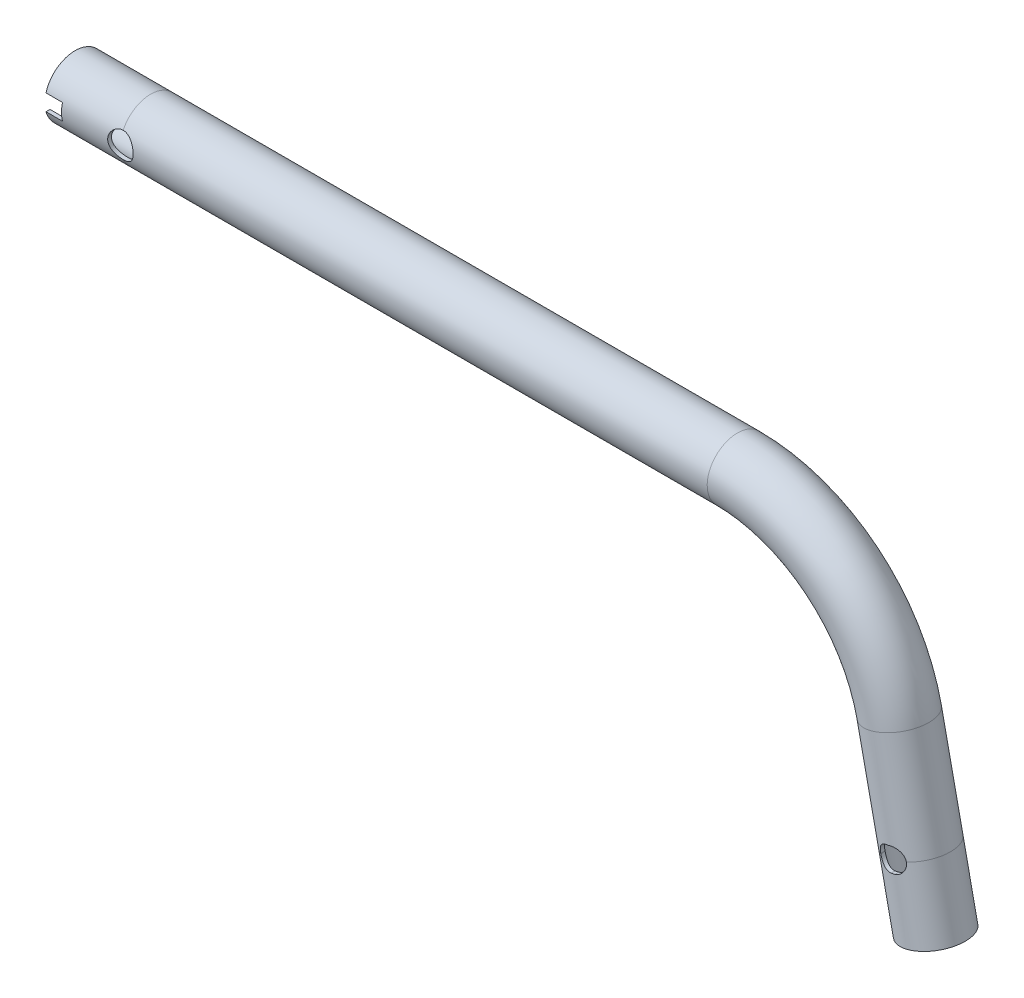
SolidWorks part; units mm, degrees
ref_plane "Front Plane" through (0, 0, 0) normal (0, 0, 1) x (1, 0, 0)
ref_plane "Top Plane" through (0, 0, 0) normal (0, 1, 0) x (1, 0, 0)
ref_plane "Right Plane" through (0, 0, 0) normal (1, 0, 0) x (0, 0, -1)
sketch "Sketch1" plane through (0, 0, 0) normal (0, 0, 1) x (1, 0, 0)
  line L0 (0, 0) -> (184.3746, 0)
  line L1 (235.2383, -41.1886) -> (242, -73)
  line L2 (0, 0) -> (-23.7238, 0)
  line L3 (242, -73) -> (246.6762, -95)
  arc A0 (235.2383, -41.1886) -> (184.3746, 0) centre (184.3746, -52) ccw
  point P10 (242, -73)
  dimension "D2" = 52
  dimension "D1" = 78
  dimension "D3" = 242
  dimension "D4" = 73
  dimension "D5" = 270.4
  dimension "D6" = 95
ref_plane "Plane1" through (-23.7238, 0, 0) normal (-1, 0, 0) x (0, 0, 1)
sketch "Sketch2" plane through (-23.7238, 0, 0) normal (-1, 0, 0) x (0, 0, 1)
  circle A0 centre (0, 0) radius 9.5
  circle A1 centre (0, 0) radius 8.3
  dimension "D1" = 1.2
sweep "Sweep1" add profiles "Sketch2" path "Sketch1"
sketch "Sketch3" plane through (0, 0, 0) normal (0, 0, 1) x (1, 0, 0)
  line L0 (242, -73) -> (246.0104, -72.1476) construction
  line L1 (232.7076, -74.9752) -> (251.2924, -71.0248) construction
  line L2 (242, -73) -> (241.2619, -69.5276) construction
  line L3 (246.0278, -72.2293) -> (245.993, -72.0658)
  line L4 (241.8418, -69.37) -> (240.668, -69.6195)
  line L5 (237.9722, -73.7707) -> (238.007, -73.9342)
  line L6 (242.1582, -76.63) -> (243.332, -76.3805)
  arc A0 (242.1582, -76.63) -> (238.007, -73.9342) centre (241.4305, -73.2065) cw
  arc A1 (243.332, -76.3805) -> (246.0278, -72.2293) centre (242.6043, -72.957) ccw
  arc A2 (245.993, -72.0658) -> (241.8418, -69.37) centre (242.5695, -72.7935) ccw
  arc A3 (240.668, -69.6195) -> (237.9722, -73.7707) centre (241.3957, -73.043) ccw
  point P8 (246.0104, -72.1476)
  point P14 (246.7555, -75.6528)
  point P17 (245.2653, -68.6423)
  point P20 (237.2445, -70.3472)
  dimension "D6" = 3.5
  dimension "D1" = 4.1
  dimension "D2" = 3.55
  dimension "D3" = 90
  dimension "D4" = 7.1671
  dimension "D5" = 8.2
extrude "Cut-Extrude1" cut sketch "Sketch3" against normal up to next and the other way up to next
sketch "Sketch4" plane through (0, 0, 0) normal (0, 0, 1) x (1, 0, 0)
  line L0 (0, -9.5) -> (0, 9.5) construction
  circle A0 centre (0, 0) radius 4
extrude "Cut-Extrude2" cut sketch "Sketch4" along normal up to next
sketch "Sketch5" plane through (0, 0, 0) normal (0, 0, 1) x (1, 0, 0)
  line L0 (-23.7238, 0) -> (-23.7238, 2.555)
  line L1 (-23.7238, 9.5) -> (-23.7238, -9.5) construction
  line L2 (-23.7238, 2.555) -> (-18.5238, 2.555)
  line L3 (-18.5238, 2.555) -> (-18.5238, -2.555)
  line L4 (-18.5238, -2.555) -> (-23.7238, -2.555)
  line L5 (-23.7238, -2.555) -> (-23.7238, 0)
  dimension "D1" = 5.2
  dimension "D2" = 5.11
extrude "Cut-Extrude3" cut sketch "Sketch5" against normal through all and the other way through all
